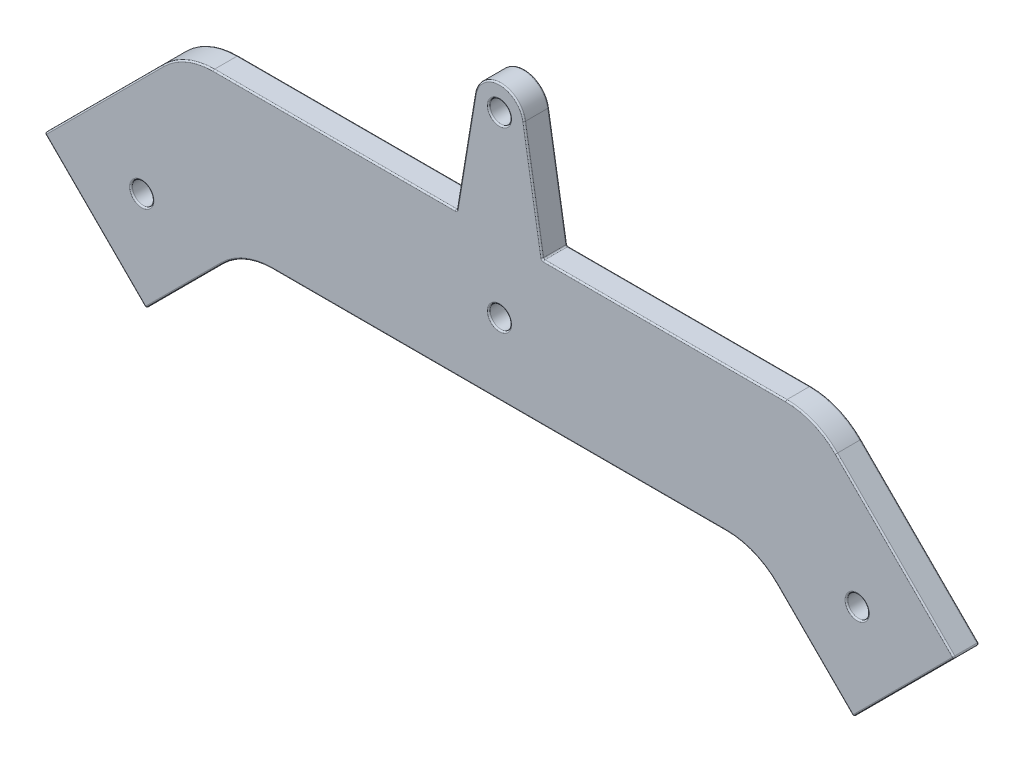
SolidWorks part; units mm, degrees
ref_plane "Front Plane" through (0, 0, 0) normal (0, 0, 1) x (1, 0, 0)
ref_plane "Top Plane" through (0, 0, 0) normal (0, 1, 0) x (1, 0, 0)
ref_plane "Right Plane" through (0, 0, 0) normal (1, 0, 0) x (0, 0, -1)
sketch "Sketch1" plane through (0, 0, 0) normal (0, 0, 1) x (1, 0, 0)
  line L0 (-100, 0) -> (100, 0) construction
  line L1 (-100, 0) -> (0, 100) construction
  line L2 (0, 100) -> (100, 0) construction
  line L3 (0, 0) -> (-50, 50) construction
  line L4 (-50, 50) -> (0, 0) construction
  line L5 (-40, 60) -> (40, 60) construction
  line L6 (0, 100) -> (0, 60) construction
  circle A0 centre (-100, 0) radius 20
  circle A1 centre (0, 0) radius 20
  circle A2 centre (100, 0) radius 20
  point P5 (0, 0)
  dimension "D5" = 40
  dimension "D1" = 200
  dimension "D2" = 90
  dimension "D3" = 90
  dimension "D4" = 80
sketch "Sketch2" plane through (0, 0, 0) normal (0, 0, 1) x (1, 0, 0)
  line L0 (-56.5165, 43.4835) -> (-40, 60) construction
  line L1 (-100, 0) -> (0, 100) construction
  line L2 (-40, 60) -> (40, 60) construction
  line L3 (40, 60) -> (86.565, 13.435) construction
  line L4 (0, 100) -> (100, 0) construction
  line L5 (-49.4454, 36.4124) -> (-35.8579, 50)
  line L6 (-35.8579, 50) -> (35.8579, 50)
  line L7 (35.8579, 50) -> (79.4939, 6.364)
  line L8 (-63.5876, 50.5546) -> (-44.1421, 70)
  line L9 (-44.1421, 70) -> (44.1421, 70)
  line L10 (44.1421, 70) -> (93.636, 20.5061)
  line L11 (-63.5876, 50.5546) -> (-49.4454, 36.4124)
  line L12 (93.636, 20.5061) -> (79.4939, 6.364)
  line L13 (81.9688, 8.8388) -> (95.4038, -4.5962)
  line L14 (91.1612, 18.0312) -> (104.5962, 4.5962)
  line L15 (75.9584, 9.8995) -> (90.1005, 24.0416) construction
  line L16 (0, 100) -> (0, 60) construction
  line L17 (-6, 70) -> (-3.4326, 85.5452)
  line L18 (6, 70) -> (3.4532, 85.4203)
  circle A0 centre (100, 0) radius 3.5
  circle A1 centre (100, 0) radius 10 construction
  arc A2 (95.4038, -4.5962) -> (104.5962, 4.5962) centre (100, 0) ccw
  circle A3 centre (100, 0) radius 0.5
  circle A4 centre (100, 0) radius 6.5 construction
  circle A5 centre (79.4939, 13.435) radius 1.8428
  circle A6 centre (86.565, 20.5061) radius 1.8428
  circle A7 centre (0, 60) radius 1.5
  circle A8 centre (0, 84.85) radius 1.5
  arc A9 (3.4532, 85.4203) -> (-3.4532, 85.4203) centre (0, 84.85) ccw
  circle A10 centre (0, 84.85) radius 3.5 construction
  circle A11 centre (-50, 50) radius 1.5
  dimension "D4" = 20
  dimension "D5" = 7
  dimension "D11" = 3
  dimension "D15" = 3
  dimension "D3" = 27.5
  dimension "D8" = 19
  dimension "D9" = 5
  dimension "D10" = 5
  dimension "5" = 5
  dimension "D12" = 14.85
  dimension "D7" = 6
  dimension "D14" = 6
  dimension "D1" = 10
  dimension "D2" = 10
  dimension "D6" = 3
  dimension "D13" = 2
sketch "Sketch3" plane through (0, 0, 0) normal (0, 0, 1) x (1, 0, 0)
  line L0 (-100, 0) -> (100, 0) construction
  line L1 (-86.6719, 13.3281) -> (-50, 50) construction
  line L2 (-24.0416, 9.8995) -> (-9.8995, 24.0416) construction
  line L3 (-50, 50) -> (-13.435, 13.435) construction
  line L4 (0, 0) -> (-50, 50) construction
  line L5 (-79.4939, 6.364) -> (-50, 35.8579)
  line L6 (-50, 35.8579) -> (-20.5061, 6.364)
  line L7 (-93.636, 20.5061) -> (-50, 64.1421)
  line L8 (-50, 64.1421) -> (-6.364, 20.5061)
  line L9 (-81.6799, 4.1779) -> (-50, 35.8579) construction
  line L10 (-95.8221, 18.3201) -> (-50, 64.1421) construction
  line L11 (-93.636, 20.5061) -> (-79.4939, 6.364)
  line L12 (-20.5061, 6.364) -> (-6.364, 20.5061)
  line L13 (-81.9688, 8.8388) -> (-95.4038, -4.5962)
  line L14 (-91.1612, 18.0312) -> (-104.5962, 4.5962)
  line L15 (-18.0312, 8.8388) -> (-4.5962, -4.5962)
  line L16 (-8.8388, 18.0312) -> (4.5962, 4.5962)
  line L17 (-88.751, 11.249) -> (-50, 50) construction
  line L18 (-90.1005, 24.0416) -> (-76.1469, 10.088) construction
  circle A0 centre (-100, 0) radius 10 construction
  circle A1 centre (-100, 0) radius 3.5
  circle A2 centre (0, 0) radius 10 construction
  circle A3 centre (0, 0) radius 3.5
  arc A4 (-4.5962, -4.5962) -> (4.5962, 4.5962) centre (0, 0) ccw
  arc A5 (-104.5962, 4.5962) -> (-95.4038, -4.5962) centre (-100, 0) ccw
  circle A6 centre (-86.565, 20.5061) radius 1
  circle A7 centre (0, 0) radius 6.5 construction
  circle A8 centre (-100, 0) radius 6.5 construction
  circle A9 centre (-79.4939, 13.435) radius 1
  circle A10 centre (-20.5061, 13.435) radius 1
  circle A11 centre (-13.435, 20.5061) radius 1
  circle A12 centre (-50, 50) radius 1.5 construction
  circle A13 centre (-50, 50) radius 1.5
  dimension "D1" = 20
  dimension "D2" = 7
  dimension "D9" = 2
  dimension "D7" = 19
  dimension "D8" = 19
  dimension "D10" = 5
  dimension "D11" = 5
  dimension "D12" = 5
  dimension "D13" = 5
  dimension "D14" = 5
  dimension "D15" = 5
  dimension "D3" = 3
  dimension "D4" = 3
  dimension "D5" = 10
  dimension "D6" = 10
sketch "Sketch4" plane through (0, 0, 0) normal (0, 0, 1) x (1, 0, 0)
  line L1 (57.5, 96.35) -> (57.5, 86.35)
  line L2 (57.5, 86.35) -> (44.1421, 70)
  line L3 (44.1421, 70) -> (-44.1421, 70)
  line L4 (-44.1421, 70) -> (-57.5, 86.35)
  line L5 (-57.5, 86.35) -> (-57.5, 96.35)
  line L7 (-57.5, 96.35) -> (57.5, 96.35)
  line L8 (-4, 60) -> (-4, 70)
  line L9 (4, 60) -> (4, 70)
  line L10 (-22.4799, 87.85) -> (22.5201, 87.85) construction
  line L11 (-22.4799, 92.35) -> (22.5201, 92.35)
  line L12 (-22.4799, 83.35) -> (22.5201, 83.35)
  circle A0 centre (0, 60) radius 1.5 construction
  circle A1 centre (0, 60) radius 1.5
  arc A2 (-4, 60) -> (4, 60) centre (0, 60) ccw
  circle A3 centre (0, 60) radius 4 construction
  arc A4 (-22.4799, 92.35) -> (-22.4799, 83.35) centre (-22.4799, 87.85) ccw
  arc A5 (22.5201, 83.35) -> (22.5201, 92.35) centre (22.5201, 87.85) ccw
  circle A6 centre (0, 84.85) radius 1.5 construction
  point P0 (0, 96.35)
  point P22 (0.0201, 87.85)
  dimension "D1" = 115
  dimension "D2" = 10
  dimension "D4" = 45
  dimension "D5" = 9
  dimension "D6" = 45
  dimension "D7" = 4
  dimension "D3" = 2.5
sketch "Sketch6" plane through (0, 0, 0) normal (0, 0, 1) x (1, 0, 0)
  line L2 (6, 70) -> (3.4532, 85.4203) construction
  line L3 (-6, 70) -> (-3.4326, 85.5452) construction
  line L4 (-50, 50) -> (-56.5165, 43.4835) construction
  line L5 (-50, 50) -> (-40, 60) construction
  line L6 (6, 70) -> (3.4532, 85.4203)
  line L7 (-6, 70) -> (-3.4326, 85.5452)
  line L8 (93.636, 20.5061) -> (44.1421, 70)
  line L9 (79.4939, 6.364) -> (93.636, 20.5061)
  line L10 (35.8579, 50) -> (79.4939, 6.364)
  line L11 (-35.8579, 50) -> (35.8579, 50)
  line L12 (-49.4454, 36.4124) -> (-35.8579, 50)
  line L13 (-63.5876, 50.5546) -> (-49.4454, 36.4124)
  line L14 (-44.1421, 70) -> (-63.5876, 50.5546)
  line L15 (44.1421, 70) -> (-44.1421, 70)
  line L16 (63.5876, 50.5546) -> (44.1421, 70)
  line L18 (35.8579, 50) -> (49.4454, 36.4124)
  line L19 (-35.8579, 50) -> (35.8579, 50)
  line L20 (-49.4454, 36.4124) -> (-35.8579, 50)
  line L21 (-63.5876, 50.5546) -> (-49.4454, 36.4124)
  line L22 (-44.1421, 70) -> (-63.5876, 50.5546)
  line L23 (44.1421, 70) -> (6, 70)
  line L24 (-6, 70) -> (-44.1421, 70)
  line L25 (-40, 60) -> (40, 60) construction
  line L26 (49.4454, 36.4124) -> (63.5876, 50.5546)
  line L27 (40, 60) -> (56.5165, 43.4835) construction
  circle A1 centre (50, 50) radius 1.5
  circle A5 centre (0, 84.85) radius 1.5
  circle A6 centre (0, 84.85) radius 1.5
  circle A7 centre (0, 60) radius 1.5
  circle A8 centre (0, 60) radius 1.5
  circle A13 centre (-50, 50) radius 1.5
  circle A14 centre (-50, 50) radius 1.5
  arc A15 (3.4532, 85.4203) -> (-3.4532, 85.4203) centre (0, 84.85) ccw construction
  arc A17 (3.4532, 85.4203) -> (-3.4532, 85.4203) centre (0, 84.85) ccw
  point P2 (0, 0)
  point P11 (0, 0)
  dimension "D6" = 3
  dimension "D1" = 20
  dimension "D2" = 20
  dimension "D3" = 0
  dimension "D4" = 0
  dimension "D5" = 0
  dimension "D8" = 0
extrude "Boss-Extrude1" add sketch "Sketch6" along normal blind 3.5
fillet "Fillet1" radius 10 4 edges at (35.8579, 50, 1.75) (-35.8579, 50, 1.75) (44.1421, 70, 1.75) (-44.1421, 70, 1.75)
fillet "Fillet2" radius 0.2 46 edges at (51.5, 50, 0) (1.5, 84.85, 0) (1.5, 60, 0) (-48.5, 50, 0) (4.7266, 77.7102, 0) (0, 88.35, 0) (-4.7266, 77.7102, 0) (-23, 70, 0) (-55.3293, 58.8128, 0) (-56.5165, 43.4835, 0) (-44.1161, 41.7417, 0) (0, 50, 0) (44.1161, 41.7417, 0) (56.5165, 43.4835, 0) (55.3293, 58.8128, 0) (23, 70, 0) (51.5, 50, 3.5) (1.5, 84.85, 3.5) (1.5, 60, 3.5) (-48.5, 50, 3.5) (4.7266, 77.7102, 3.5) (0, 88.35, 3.5) (-4.7266, 77.7102, 3.5) (-55.3293, 58.8128, 3.5) (-56.5165, 43.4835, 3.5) (-44.1161, 41.7417, 3.5) (0, 50, 3.5) (44.1161, 41.7417, 3.5) (56.5165, 43.4835, 3.5) (55.3293, 58.8128, 3.5) (23, 70, 3.5) (6, 70, 1.75) (63.5876, 50.5546, 1.75) (49.4454, 36.4124, 1.75) (-49.4454, 36.4124, 1.75) (-63.5876, 50.5546, 1.75) (-6, 70, 1.75) (-43.8268, 69.2388, 0) (43.8268, 69.2388, 0) (-43.8268, 69.2388, 3.5) (43.8268, 69.2388, 3.5) (35.5426, 49.2388, 0) (35.5426, 49.2388, 3.5) (-35.5426, 49.2388, 0) (-35.5426, 49.2388, 3.5) (-23, 70, 3.5)
